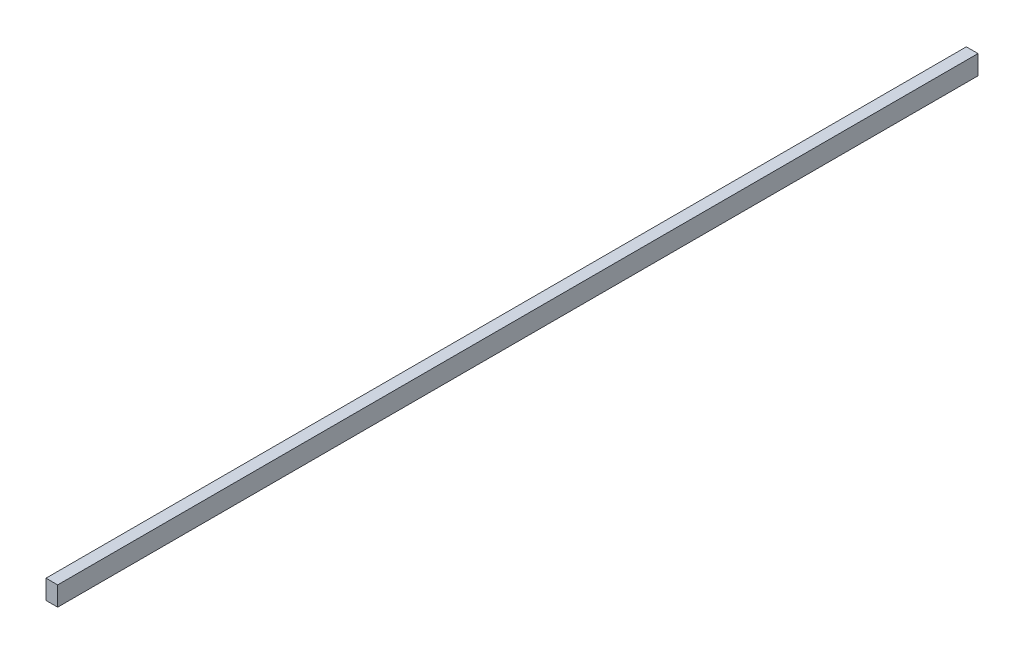
SolidWorks part; units mm, degrees
ref_plane "Front" through (0, 0, 0) normal (0, 0, 1) x (1, 0, 0)
ref_plane "Top" through (0, 0, 0) normal (0, 1, 0) x (1, 0, 0)
ref_plane "Right" through (0, 0, 0) normal (1, 0, 0) x (0, 0, -1)
sketch "Esquisse1" plane through (0, 0, 0) normal (0, 0, 1) x (1, 0, 0)
  line L1 (0, 0) -> (38, 0)
  line L2 (0, 0) -> (0, 63)
  line L3 (0, 63) -> (38, 63)
  line L4 (38, 0) -> (38, 63)
  dimension "D1" = 38
  dimension "D2" = 63
extrude "Boss.-Extru.1" add sketch "Esquisse1" along normal blind 3000
